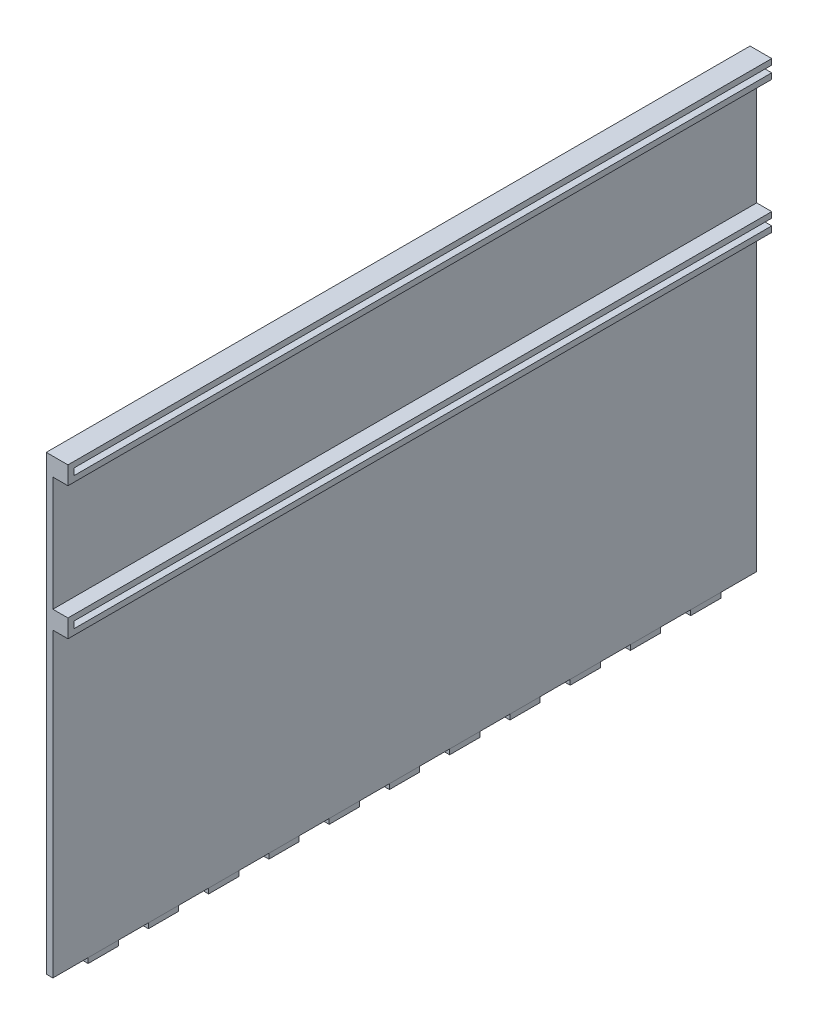
SolidWorks part; units mm, degrees
ref_plane "Front Plane" through (0, 0, 0) normal (0, 0, 1) x (1, 0, 0)
ref_plane "Top Plane" through (0, 0, 0) normal (0, 1, 0) x (1, 0, 0)
ref_plane "Right Plane" through (0, 0, 0) normal (1, 0, 0) x (0, 0, -1)
sketch "草图4" plane through (0, 0, 0) normal (1, 0, 0) x (0, 0, -1)
  line L1 (116.8, -75) -> (-116.8, -75)
  line L2 (116.8, -75) -> (116.8, 75)
  line L3 (116.8, 75) -> (-116.8, 75)
  line L4 (-116.8, -75) -> (-116.8, 75)
  line L5 (116.8, -75) -> (-116.8, 75) construction
  line L6 (116.8, 75) -> (-116.8, -75) construction
  point P0 (0, 0)
  dimension "D1" = 233.6
  dimension "D2" = 150
extrude "凸台-拉伸2" add sketch "草图4" along normal blind 2.2
sketch "草图6" plane through (0, -75, 0) normal (0, -1, 0) x (1, 0, 0)
  line L6 (2.1, 15) -> (2.1, 25)
  line L10 (2.1, 15) -> (0.1, 15)
  line L11 (2.1, -5) -> (0.1, -5)
  line L12 (2.1, -5) -> (2.1, 5)
  line L13 (2.1, 5) -> (0.1, 5)
  line L14 (0.1, -5) -> (0.1, 5)
  line L15 (2.1, -5) -> (0.1, 5) construction
  line L16 (2.1, 5) -> (0.1, -5) construction
  line L17 (0.1, 15) -> (0.1, 25)
  line L18 (2.1, 25) -> (0.1, 25)
  line L19 (2.1, 35) -> (2.1, 45)
  line L20 (2.1, 35) -> (0.1, 35)
  line L21 (0.1, 35) -> (0.1, 45)
  line L22 (2.1, 45) -> (0.1, 45)
  line L23 (2.1, 55) -> (2.1, 65)
  line L24 (2.1, 55) -> (0.1, 55)
  line L25 (0.1, 55) -> (0.1, 65)
  line L26 (2.1, 65) -> (0.1, 65)
  line L27 (2.1, 75) -> (2.1, 85)
  line L28 (2.1, 75) -> (0.1, 75)
  line L29 (0.1, 75) -> (0.1, 85)
  line L30 (2.1, 85) -> (0.1, 85)
  line L31 (2.1, 95) -> (2.1, 105)
  line L32 (2.1, 95) -> (0.1, 95)
  line L33 (0.1, 95) -> (0.1, 105)
  line L34 (2.1, 105) -> (0.1, 105)
  line L35 (2.1, -25) -> (2.1, -15)
  line L36 (2.1, -25) -> (0.1, -25)
  line L37 (0.1, -25) -> (0.1, -15)
  line L38 (2.1, -15) -> (0.1, -15)
  line L39 (2.1, -45) -> (2.1, -35)
  line L40 (2.1, -45) -> (0.1, -45)
  line L41 (0.1, -45) -> (0.1, -35)
  line L42 (2.1, -35) -> (0.1, -35)
  line L43 (2.1, -65) -> (2.1, -55)
  line L44 (2.1, -65) -> (0.1, -65)
  line L45 (0.1, -65) -> (0.1, -55)
  line L46 (2.1, -55) -> (0.1, -55)
  line L47 (2.1, -85) -> (2.1, -75)
  line L48 (2.1, -85) -> (0.1, -85)
  line L49 (0.1, -85) -> (0.1, -75)
  line L50 (2.1, -75) -> (0.1, -75)
  line L51 (2.1, -105) -> (2.1, -95)
  line L52 (2.1, -105) -> (0.1, -105)
  line L53 (0.1, -105) -> (0.1, -95)
  line L54 (2.1, -95) -> (0.1, -95)
  point P6 (1.1, 0)
  dimension "D1" = 2
  dimension "D2" = 10
  dimension "D3" = 6
extrude "凸台-拉伸3" add sketch "草图6" along normal blind 1.8
sketch "草图7" plane through (2.2, 0, 0) normal (1, 0, 0) x (0, 0, -1)
  line L0 (116.8, 25) -> (-116.8, 25)
  line L5 (-116.8, -75) -> (116.8, -75) construction
  line L6 (-116.8, 75) -> (-116.8, -75) construction
  line L8 (116.8, -75) -> (116.8, 75) construction
  line L14 (-116.8, 31) -> (-116.8, 25)
  line L15 (116.8, 31) -> (116.8, 25)
  line L16 (-116.8, 31) -> (116.8, 31)
  line L17 (116.8, 69) -> (116.8, 75)
  line L18 (-116.8, 69) -> (116.8, 69)
  line L19 (-116.8, 69) -> (-116.8, 75)
  line L20 (116.8, 75) -> (-116.8, 75)
  dimension "D1" = 100
  dimension "D2" = 6
extrude "凸台-拉伸4" add sketch "草图7" along normal blind 5
sketch "草图8" plane through (7.2, 0, 0) normal (1, 0, 0) x (0, 0, -1)
  line L0 (0, 31) -> (0, 25)
  line L1 (116.8, 31) -> (-116.8, 31) construction
  line L2 (-116.8, 25) -> (116.8, 25) construction
  line L4 (-114.8, 29.1) -> (-114.8, 26.9)
  line L5 (116.8, 26.9) -> (-116.8, 26.9)
  line L6 (116.8, 26.9) -> (116.8, 29.1)
  line L7 (116.8, 29.1) -> (-116.8, 29.1)
  line L9 (116.8, 26.9) -> (-116.8, 29.1) construction
  line L10 (116.8, 29.1) -> (-116.8, 26.9) construction
  line L11 (116.8, 73.1) -> (116.8, 70.9)
  line L15 (116.8, 73.1) -> (-116.8, 73.1)
  line L16 (-114.8, 70.9) -> (-114.8, 73.1)
  line L17 (116.8, 70.9) -> (-116.8, 70.9)
  point P6 (0, 28)
  line M9 (116.8, 25) -> (116.8, 31)
  dimension "D1" = 2.2
extrude "切除-拉伸1" cut sketch "草图8" against normal blind 3 contours L0 L7 L4 L5 | L7 L0 L5 M9 | L17 L11 L15 L16
